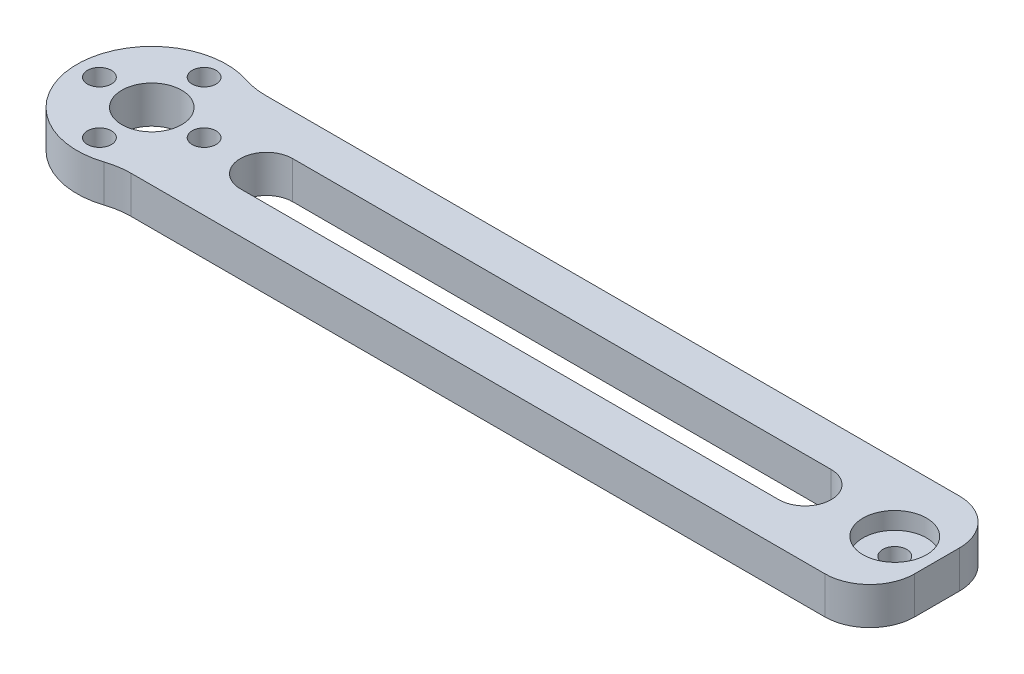
SolidWorks part; units mm, degrees
material "环氧树脂,未充填"
ref_plane "前视基准面" through (0, 0, 0) normal (0, 0, 1) x (1, 0, 0)
ref_plane "上视基准面" through (0, 0, 0) normal (0, 1, 0) x (1, 0, 0)
ref_plane "右视基准面" through (0, 0, 0) normal (1, 0, 0) x (0, 0, -1)
other "Configuration Table"
sketch "草图1" plane through (0, 0, 0) normal (0, 1, 0) x (1, 0, 0)
  line L0 (0, 0) -> (-9, 0) construction
  line L1 (0, 9) -> (99, 9)
  line L2 (105, 3) -> (105, -3)
  line L3 (99, -9) -> (0, -9)
  line L4 (0, 0) -> (99.34, 0) construction
  line L5 (15.34, 0) -> (87.34, 0) construction
  line L6 (15.34, 3.5) -> (87.34, 3.5)
  line L7 (15.34, -3.5) -> (87.34, -3.5)
  circle A0 centre (0, 0) radius 4
  circle A1 centre (0, 0) radius 9
  circle A2 centre (0, 0) radius 7 construction
  circle A4 centre (-7, 0) radius 1.6
  circle A5 centre (0, 7) radius 1.6
  circle A6 centre (7, 0) radius 1.6
  circle A7 centre (0, -7) radius 1.6
  circle A8 centre (99.34, 0) radius 1.6
  arc A9 (15.34, 3.5) -> (15.34, -3.5) centre (15.34, 0) ccw
  arc A10 (87.34, -3.5) -> (87.34, 3.5) centre (87.34, 0) ccw
  arc A11 (105, -3) -> (99, -9) centre (99, -3) cw
  arc A12 (99, 9) -> (105, 3) centre (99, 3) cw
  point P17 (0, 0)
  point P23 (51.34, 0)
  point P32 (105, 9)
  dimension "D1" = 18
  dimension "D2" = 8
  dimension "D3" = 14
  dimension "D4" = 3.2
  dimension "D7" = 3.2
  dimension "D12" = 3.5
  dimension "D13" = 6
  dimension "D6" = 105
  dimension "D8" = 9
  dimension "D9" = 5.66
  dimension "D10" = 72
  dimension "D11" = 12
  dimension "D5" = 4
extrude "凸台-拉伸1" add sketch "草图1" along normal blind 5 contours A12 L1 A1 L3 A11 L2 A10 L7 A9 L6 A8 | A1 A7 A6 A5 A4 A0
sketch "草图2" plane through (0, 5, 0) normal (0, 1, 0) x (1, 0, 0)
  circle A0 centre (99.34, 0) radius 4.25
  dimension "D1" = 8.5
extrude "切除-拉伸1" cut sketch "草图2" against normal blind 2.3
sketch "草图3" plane through (0, 5, 0) normal (0, 1, 0) x (1, 0, 0)
  circle A0 centre (0, 0) radius 10
  circle A1 centre (0, 0) radius 9
  dimension "D1" = 18
  dimension "D2" = 20
extrude "凸台-拉伸2" add sketch "草图3" against normal blind 5
fillet "圆角1" radius 10 2 edges at (4.3589, 2.5, 9) (4.3589, 2.5, -9)
